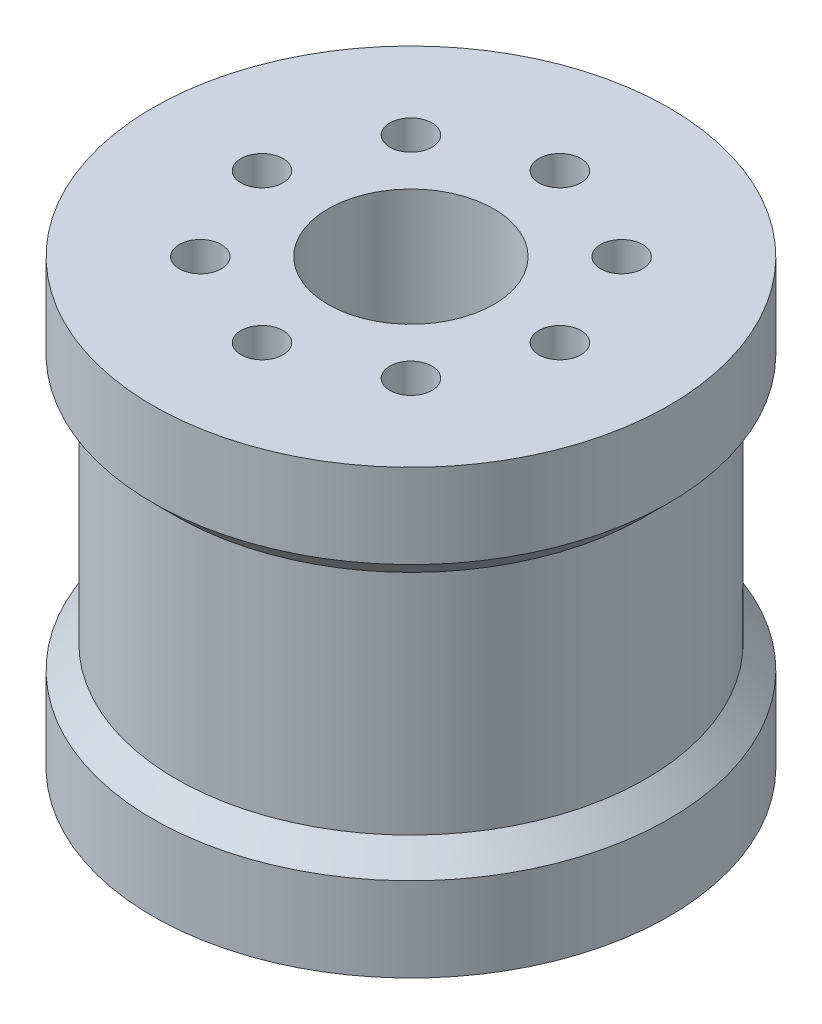
SolidWorks part; units mm, degrees
ref_plane "Front Plane" through (0, 0, 0) normal (0, 0, 1) x (1, 0, 0)
ref_plane "Top Plane" through (0, 0, 0) normal (0, 1, 0) x (1, 0, 0)
ref_plane "Right Plane" through (0, 0, 0) normal (1, 0, 0) x (0, 0, -1)
sketch "Sketch1" plane through (0, 0, 0) normal (0, 0, 1) x (1, 0, 0)
  line L0 (0, 0) -> (0, 21) construction
  line L1 (-3, 0) -> (-3, 21)
  line L2 (-3, 0) -> (-12.25, 0)
  line L3 (-12.25, 0) -> (-12.25, 4)
  line L4 (-12.25, 4) -> (-11.15, 5.1)
  line L5 (-11.15, 5.1) -> (-11.15, 15.9)
  line L6 (-11.15, 15.9) -> (-12.25, 17)
  line L7 (-12.25, 17) -> (-12.25, 21)
  line L8 (-12.25, 21) -> (-3, 21)
  line L9 (-3, 0) -> (0, 0) construction
  line L10 (-3, 21) -> (0, 21) construction
  line L11 (-12.25, 17) -> (-12.25, 4) construction
  point P10 (-7.625, 0)
  point P12 (-2.8129, 0)
  point P13 (-3.7959, 0)
  dimension "D1" = 12.25
  dimension "D2" = 11.15
  dimension "D3" = 21
  dimension "D4" = 4
  dimension "D5" = 4
  dimension "D6" = 45
  dimension "D7" = 45
  dimension "D8" = 3
revolve "Revolve1" add sketch "Sketch1" angle 360 about L0
sketch "Sketch2" plane through (0, 21, 0) normal (0, 1, 0) x (1, 0, 0)
  line L0 (0, 10.116) -> (0, 0) construction
  line L1 (5, -5) -> (-5, -5) construction
  line L2 (5, -5) -> (5, 5) construction
  line L3 (5, 5) -> (-5, 5) construction
  line L4 (-5, -5) -> (-5, 5) construction
  line L5 (5, -5) -> (-5, 5) construction
  line L6 (5, 5) -> (-5, -5) construction
  line L7 (7.0711, 0) -> (0, 7.0711) construction
  line L8 (7.0711, 0) -> (0, -7.0711) construction
  line L9 (0, 7.0711) -> (-7.0711, 0) construction
  line L10 (0, -7.0711) -> (-7.0711, 0) construction
  line L11 (7.0711, 0) -> (-7.0711, 0) construction
  line L12 (0, 7.0711) -> (0, -7.0711) construction
  circle A0 centre (0, 0) radius 3.935
  circle A1 centre (-5, 5) radius 1
  circle A2 centre (5, 5) radius 1
  circle A3 centre (5, -5) radius 1
  circle A4 centre (-5, -5) radius 1
  circle A5 centre (-7.0711, 0) radius 1
  circle A6 centre (0, 7.0711) radius 1
  circle A7 centre (7.0711, 0) radius 1
  circle A8 centre (0, -7.0711) radius 1
  point P19 (0, 0)
  dimension "D1" = 7.87
  dimension "D3" = 2
  dimension "D2" = 45
  dimension "D4" = 10
  dimension "D5" = 45
  dimension "D6" = 10
extrude "Cut-Extrude1" cut sketch "Sketch2" against normal blind 45
